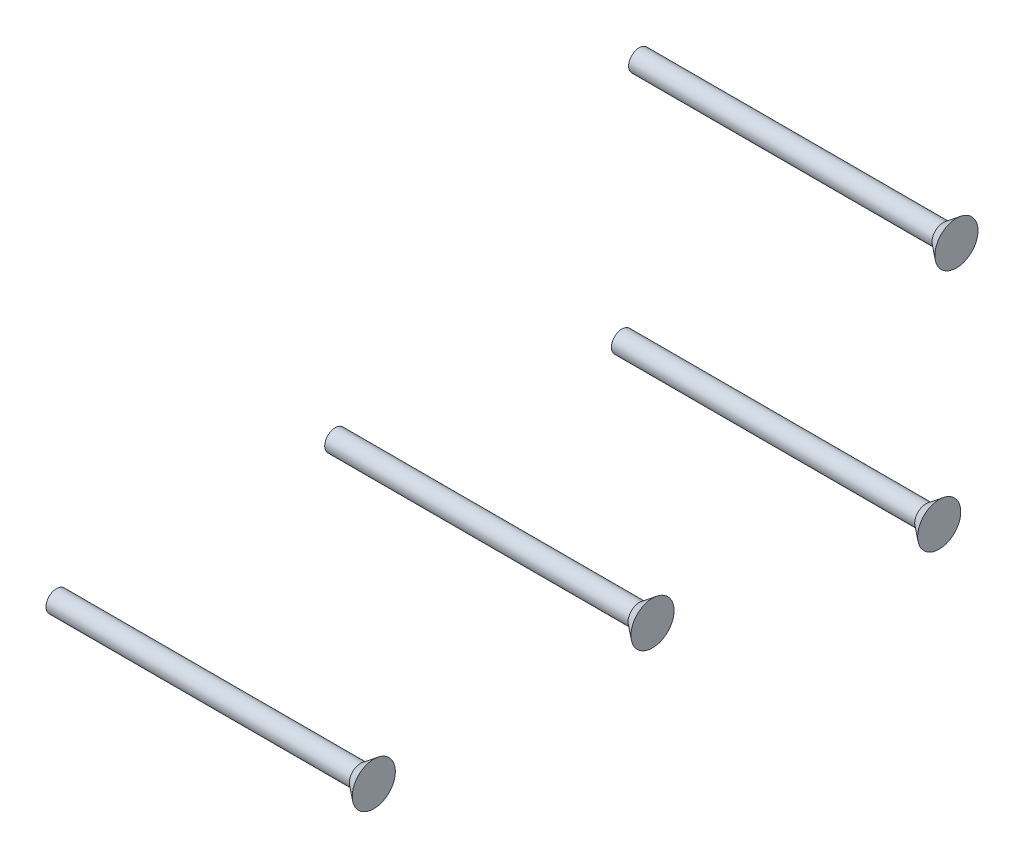
SolidWorks part; units mm, degrees
ref_plane "Front Plane" through (0, 0, 0) normal (0, 0, 1) x (1, 0, 0)
ref_plane "Top Plane" through (0, 0, 0) normal (0, 1, 0) x (1, 0, 0)
ref_plane "Right Plane" through (0, 0, 0) normal (1, 0, 0) x (0, 0, -1)
sketch "Sketch1" plane through (0, 0, 0) normal (1, 0, 0) x (0, 0, -1)
  line L0 (-53.34, 0) -> (0, 0) construction
  line L1 (0, 0) -> (54.864, -11.0719) construction
  line L2 (54.864, -11.0719) -> (58.166, 33.8861) construction
  point P0 (-53.34, 0)
  point P1 (0, 0)
  point P2 (54.864, -11.0719)
  point P3 (58.166, 33.8861)
  point P6 (0, 0)
  point P9 (0, 0)
  point P10 (0, 0)
  dimension "D1" = 3.302
  dimension "D2" = 44.958
  dimension "D3" = 53.34
  dimension "D4" = 54.864
  dimension "D5" = 11.0719
sketch "Sketch2" plane through (0, 0, 0) normal (1, 0, 0) x (0, 0, -1)
  circle A0 centre (-53.34, 0) radius 2.032
  circle A1 centre (0, 0) radius 2.032
  circle A2 centre (54.864, -11.0719) radius 2.032
  circle A3 centre (58.166, 33.8861) radius 2.032
  dimension "D1" = 4.064
extrude "Boss-Extrude1" add sketch "Sketch2" along normal blind 60.706
sketch "Sketch3" plane through (60.706, 0, 0) normal (1, 0, 0) x (0, 0, -1)
  circle A0 centre (-53.34, 0) radius 4.1275
  circle A1 centre (0, 0) radius 4.1275
  circle A2 centre (58.166, 33.8861) radius 4.1275
  circle A3 centre (54.864, -11.0719) radius 4.1275
  dimension "D1" = 8.255
extrude "Boss-Extrude2" add sketch "Sketch3" against normal blind 2.54 draft 38
